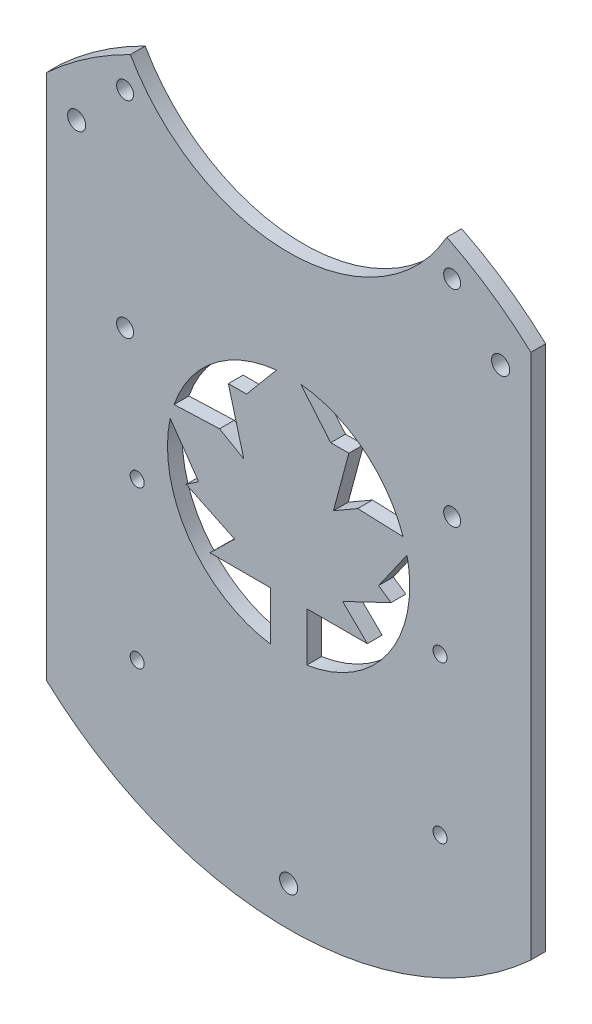
SolidWorks part; units mm, degrees
ref_plane "Front Plane" through (0, 0, 0) normal (0, 0, 1) x (1, 0, 0)
ref_plane "Top Plane" through (0, 0, 0) normal (0, 1, 0) x (1, 0, 0)
ref_plane "Right Plane" through (0, 0, 0) normal (1, 0, 0) x (0, 0, -1)
sketch "Sketch1" plane through (0, 0, 0) normal (0, 0, 1) x (1, 0, 0)
  line L0 (0, 47.9049) -> (0, -75) construction
  line L1 (-50.8, 55.1757) -> (-50.8, -55.1757)
  line L2 (50.8, 55.1757) -> (50.8, -55.1757)
  arc A0 (-33.1727, 67.265) -> (-50.8, 55.1757) centre (0, 0) ccw
  arc A1 (-33.1727, 67.265) -> (33.1727, 67.265) centre (0, 86.0049) ccw
  circle A2 centre (0, -66.675) radius 1.8987
  circle A3 centre (-44.45, 49.6966) radius 1.8987
  circle A4 centre (44.45, 49.6966) radius 1.8986
  arc A5 (-50.8, -55.1757) -> (50.8, -55.1757) centre (0, 0) ccw
  arc A6 (50.8, 55.1757) -> (33.1727, 67.265) centre (0, 0) ccw
  circle A7 centre (0, 0) radius 66.675 construction
  dimension "D8" = 3.7973
  dimension "D11" = 3.7973
  dimension "D5" = 150
  dimension "D7" = 133.35
  dimension "D2" = 66.3453
  dimension "D3" = 38.1
  dimension "D4" = 44.45
  dimension "D6" = 50.8
extrude "Boss-Extrude3" add sketch "Sketch1" along normal blind 3.0988
sketch "Sketch2" plane through (0, 0, 3.0988) normal (0, 0, 1) x (1, 0, 0)
  line L0 (0, 47.9049) -> (0, -75) construction
  line L1 (-34.925, -41.98) -> (34.925, -41.98) construction
  line L2 (-34.925, -61.03) -> (-34.925, -22.93) construction
  line L3 (-34.925, -61.03) -> (34.925, -61.03) construction
  line L4 (34.925, -61.03) -> (34.925, -22.93) construction
  line L5 (-34.925, -22.93) -> (34.925, -22.93) construction
  line L6 (0, -61.03) -> (0, -22.93) construction
  line L7 (-28.575, -55.7849) -> (-28.575, -28.1751) construction
  line L8 (-28.575, -55.7849) -> (28.575, -55.7849) construction
  line L9 (28.575, -55.7849) -> (28.575, -28.1751) construction
  line L10 (-28.575, -28.1751) -> (28.575, -28.1751) construction
  line L11 (-28.575, -55.7849) -> (28.575, -28.1751) construction
  line L12 (28.575, -55.7849) -> (-28.575, -28.1751) construction
  line L13 (-34.925, -9.1251) -> (34.925, -9.1251) construction
  line L14 (34.925, 9.9249) -> (34.925, -22.93) construction
  line L15 (-34.925, -22.93) -> (34.925, -22.93) construction
  line L16 (-34.925, 9.9249) -> (-34.925, -22.93) construction
  line L17 (-34.925, 9.9249) -> (34.925, 9.9249) construction
  line L18 (0, -22.93) -> (0, 9.9249) construction
  line L19 (-28.575, -22.93) -> (-28.575, 4.6798) construction
  line L20 (-28.575, -22.93) -> (28.575, -22.93) construction
  line L21 (28.575, -22.93) -> (28.575, 4.6798) construction
  line L22 (-28.575, 4.6798) -> (28.575, 4.6798) construction
  line L23 (-28.575, -22.93) -> (28.575, 4.6798) construction
  line L24 (28.575, -22.93) -> (-28.575, 4.6798) construction
  arc A0 (-33.1727, 67.265) -> (33.1727, 67.265) centre (0, 86.0049) ccw construction
  arc A1 (-50.8, -55.1757) -> (50.8, -55.1757) centre (0, 0) ccw construction
  circle A2 centre (-31.75, -41.98) radius 1.4732
  circle A3 centre (31.75, -41.98) radius 1.4732
  circle A4 centre (-31.75, -9.1251) radius 1.4732
  circle A5 centre (31.75, -9.1251) radius 1.4732
  point P8 (0, -41.98)
  point P25 (0, -9.1251)
  dimension "D7" = 2.9464
  dimension "D11" = 2.9464
  dimension "D1" = 57.15
  dimension "D2" = 27.6098
  dimension "D3" = 3.175
  dimension "D4" = 33.02
  dimension "D5" = 38.1
  dimension "D6" = 69.85
  dimension "D8" = 57.15
  dimension "D9" = 27.6098
  dimension "D10" = 32.8549
  dimension "D12" = 32.8549
  dimension "D13" = 69.85
  dimension "D14" = 28.575
extrude "Cut-Extrude1" cut sketch "Sketch2" against normal up to surface (3.0988 mm away) up to face at (1.8987, -66.675, 0)
sketch "Sketch3" plane through (0, 0, 3.0988) normal (0, 0, 1) x (1, 0, 0)
  line L0 (0, 47.9049) -> (0, -75) construction
  line L1 (0, 25.4) -> (0, -25.4) construction
  line L2 (8.8271, 17.78) -> (2.54, 25.2727)
  line L3 (8.8271, 17.78) -> (12.6371, 17.78)
  line L4 (12.6371, 17.78) -> (9.4043, 5.715)
  line L5 (9.4043, 5.715) -> (14.4843, 8.6479)
  line L6 (14.4843, 8.6479) -> (24.0093, 8.2894)
  line L7 (18.8681, -3.1406) -> (24.8262, 5.3684)
  line L8 (18.8681, -3.1406) -> (21.4871, -4.9356)
  line L9 (21.4871, -4.9356) -> (11.3271, -9.7979)
  line L10 (11.3271, -9.7979) -> (16.51, -14.8779)
  line L11 (16.51, -14.8779) -> (3.81, -14.8779)
  line L12 (3.81, -14.8779) -> (3.81, -25.1126)
  line L13 (-3.81, -14.8779) -> (-3.81, -25.1126)
  line L14 (-16.51, -14.8779) -> (-3.81, -14.8779)
  line L15 (-11.3271, -9.7979) -> (-16.51, -14.8779)
  line L16 (-21.4871, -4.9356) -> (-11.3271, -9.7979)
  line L17 (-18.8681, -3.1406) -> (-21.4871, -4.9356)
  line L18 (-18.8681, -3.1406) -> (-24.8262, 5.3684)
  line L19 (-14.4843, 8.6479) -> (-24.0093, 8.2894)
  line L20 (-9.4043, 5.715) -> (-14.4843, 8.6479)
  line L21 (-12.6371, 17.78) -> (-9.4043, 5.715)
  line L22 (-8.8271, 17.78) -> (-12.6371, 17.78)
  line L23 (-8.8271, 17.78) -> (-2.54, 25.2727)
  arc A0 (-33.1727, 67.265) -> (33.1727, 67.265) centre (0, 86.0049) ccw construction
  arc A1 (-50.8, -55.1757) -> (50.8, -55.1757) centre (0, 0) ccw construction
  arc A2 (3.81, -25.1126) -> (24.8262, 5.3684) centre (0, 0) ccw
  arc A3 (-24.8262, 5.3684) -> (-3.81, -25.1126) centre (0, 0) ccw
  arc A4 (-2.54, 25.2727) -> (-24.0093, 8.2894) centre (0, 0) ccw
  arc A5 (24.0093, 8.2894) -> (2.54, 25.2727) centre (0, 0) ccw
  circle A6 centre (0, 0) radius 25.4 construction
  dimension "D1" = 7.62
  dimension "D2" = 3.81
  dimension "D3" = 12.065
  dimension "D4" = 75
  dimension "D5" = 5.08
  dimension "D6" = 45
  dimension "D7" = 9.525
  dimension "D8" = 3.175
  dimension "D9" = 10.16
  dimension "D10" = 60
  dimension "D11" = 5.08
  dimension "D12" = 12.7
  dimension "D13" = 70
  dimension "D14" = 3.81
  dimension "D15" = 2.921
  dimension "D16" = 35
  dimension "D17" = 40
extrude "Cut-Extrude2" cut sketch "Sketch3" against normal up to surface (3.0988 mm away) up to face at (33.2232, -9.1251, 0)
sketch "Sketch4" plane through (0, 0, 3.0988) normal (0, 0, 1) x (1, 0, 0)
  line L0 (0, 47.9049) -> (0, -75) construction
  line L1 (-38.1, 64.09) -> (38.1, 64.09) construction
  line L2 (-38.1, 64.09) -> (-38.1, 13.29) construction
  line L3 (-38.1, 13.29) -> (38.1, 13.29) construction
  line L4 (38.1, 64.09) -> (38.1, 13.29) construction
  line L5 (0, 64.09) -> (0, 13.29) construction
  line L6 (-38.1, 38.69) -> (38.1, 38.69) construction
  arc A0 (-33.1727, 67.265) -> (33.1727, 67.265) centre (0, 86.0049) ccw construction
  arc A1 (-50.8, -55.1757) -> (50.8, -55.1757) centre (0, 0) ccw construction
  circle A2 centre (-34.29, 60.28) radius 1.778
  circle A3 centre (34.29, 60.28) radius 1.778
  circle A4 centre (34.29, 17.1) radius 1.778
  circle A5 centre (-34.29, 17.1) radius 1.778
  dimension "D3" = 3.556
  dimension "D5" = 3.81
  dimension "D6" = 3.81
  dimension "D1" = 76.2
  dimension "D2" = 50.8
  dimension "D4" = 28.575
extrude "Cut-Extrude3" cut sketch "Sketch4" against normal up to surface (3.0988 mm away) up to face at (-12.3976, 14.4374, 0)
